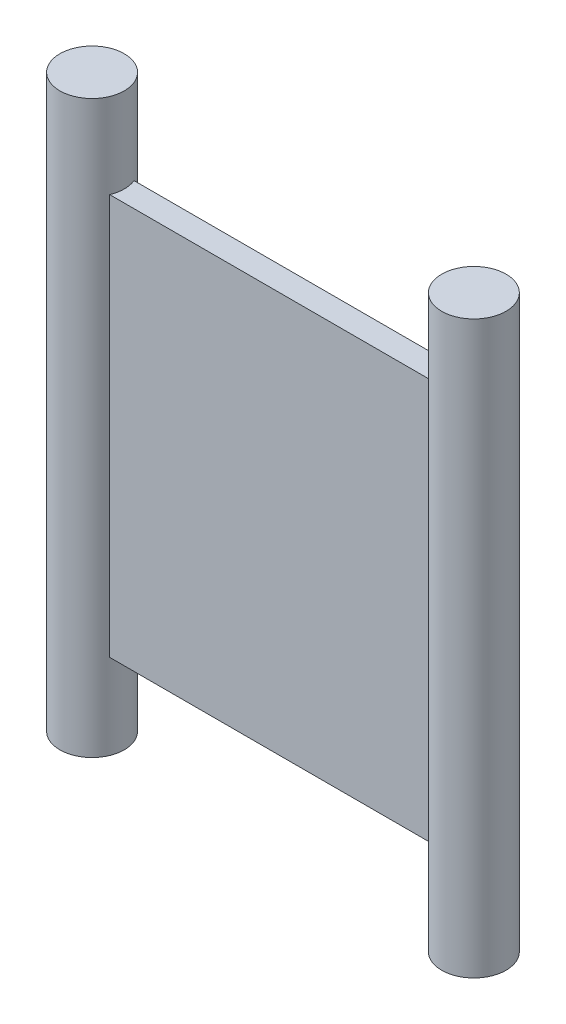
SolidWorks part; units mm, degrees
ref_plane "Front Plane" through (0, 0, 0) normal (0, 0, 1) x (1, 0, 0)
ref_plane "Top Plane" through (0, 0, 0) normal (0, 1, 0) x (1, 0, 0)
ref_plane "Right Plane" through (0, 0, 0) normal (1, 0, 0) x (0, 0, -1)
sketch "Sketch1" plane through (0, 0, 0) normal (0, 1, 0) x (1, 0, 0)
  line L1 (7.86, 0.5) -> (-7.86, 0.5)
  line L2 (7.86, 0.5) -> (7.86, -0.5)
  line L3 (7.86, -0.5) -> (-7.86, -0.5)
  line L4 (-7.86, 0.5) -> (-7.86, -0.5)
  line L5 (7.86, 0.5) -> (-7.86, -0.5) construction
  line L6 (7.86, -0.5) -> (-7.86, 0.5) construction
  point P0 (0, 0)
  dimension "D1" = 15.72
  dimension "D3" = 1
extrude "Boss-Extrude1" add sketch "Sketch1" along normal blind 16.5
ref_plane "Plane1" through (0, 8.25, 0) normal (0, 1, 0) x (1, 0, 0)
sketch "Sketch2" plane through (0, 8.25, 0) normal (0, 1, 0) x (1, 0, 0)
  line L0 (7.86, -0.5) -> (7.86, 0.5) construction
  line L1 (-7.86, 0.5) -> (-7.86, -0.5) construction
  line L2 (7.86, -0.5) -> (7.86, 0.5) construction
  line L3 (-7.86, 0.5) -> (-7.86, -0.5) construction
  circle A0 centre (-7.86, 0) radius 1.325
  circle A1 centre (7.86, 0) radius 1.325
  dimension "D1" = 2.65
extrude "Boss-Extrude2" add sketch "Sketch2" along normal mid plane 23.5
